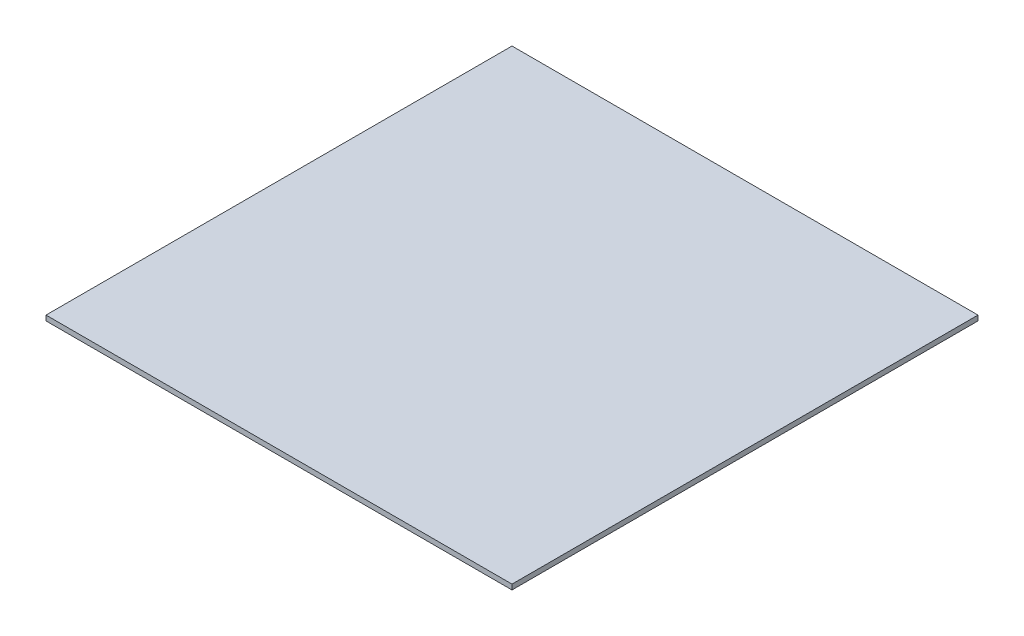
SolidWorks part; units mm, degrees
material "Plain Carbon Steel"
ref_plane "Front Plane" through (0, 0, 0) normal (0, 0, 1) x (1, 0, 0)
ref_plane "Top Plane" through (0, 0, 0) normal (0, 1, 0) x (1, 0, 0)
ref_plane "Right Plane" through (0, 0, 0) normal (1, 0, 0) x (0, 0, -1)
sketch "Sketch1" plane through (0, 0, 0) normal (0, 1, 0) x (1, 0, 0)
  line L0 (-228.6, -228.6) -> (228.6, 228.6) construction
  line L1 (-228.6, -228.6) -> (228.6, -228.6)
  line L2 (-228.6, -228.6) -> (-228.6, 228.6)
  line L3 (-228.6, 228.6) -> (228.6, 228.6)
  line L4 (228.6, -228.6) -> (228.6, 228.6)
  dimension "D1" = 457.2
  dimension "D2" = 457.2
extrude "Extrude1" add sketch "Sketch1" against normal blind 5
